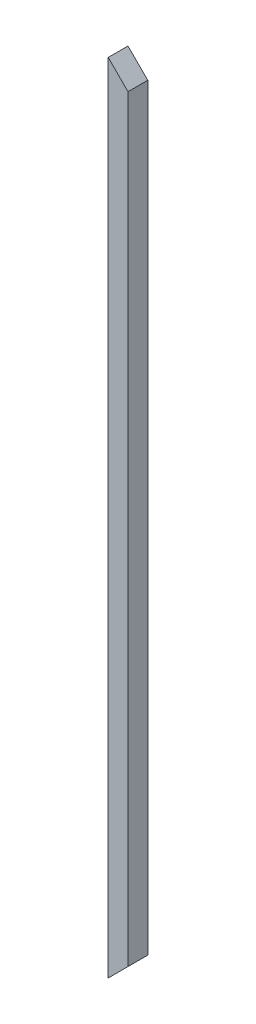
SolidWorks part; units mm, degrees
ref_plane "Спереди" through (0, 0, 0) normal (0, 0, 1) x (1, 0, 0)
ref_plane "Сверху" through (0, 0, 0) normal (0, 1, 0) x (1, 0, 0)
ref_plane "Справа" through (0, 0, 0) normal (1, 0, 0) x (0, 0, -1)
other "Configuration Table"
sketch "Эскиз1" plane through (0, 0, 0) normal (0, 1, 0) x (1, 0, 0)
  line L1 (25, 25) -> (-25, 25)
  line L2 (25, 25) -> (25, -25)
  line L3 (25, -25) -> (-25, -25)
  line L4 (-25, 25) -> (-25, -25)
  line L5 (25, 25) -> (-25, -25) construction
  line L6 (25, -25) -> (-25, 25) construction
  point P0 (0, 0)
extrude "Бобышка-Вытянуть1" add sketch "Эскиз1" along normal blind 2015.25
sketch "Эскиз7" plane through (0, 0, -25) normal (0, 0, -1) x (-1, 0, 0)
  line L0 (-25, 0) -> (25, 0)
  line L1 (25, 0) -> (-25, 50)
  line L2 (-25, 2015.25) -> (-25, 0) construction
  line L3 (-25, 50) -> (-25, 0)
  line L4 (-25, 2015.25) -> (25, 2015.25)
  line L5 (25, 2015.25) -> (-25, 1965.25)
  line L6 (-25, 1965.25) -> (-25, 2015.25)
extrude "Вырез-Вытянуть1" cut sketch "Эскиз7" against normal blind 3000
